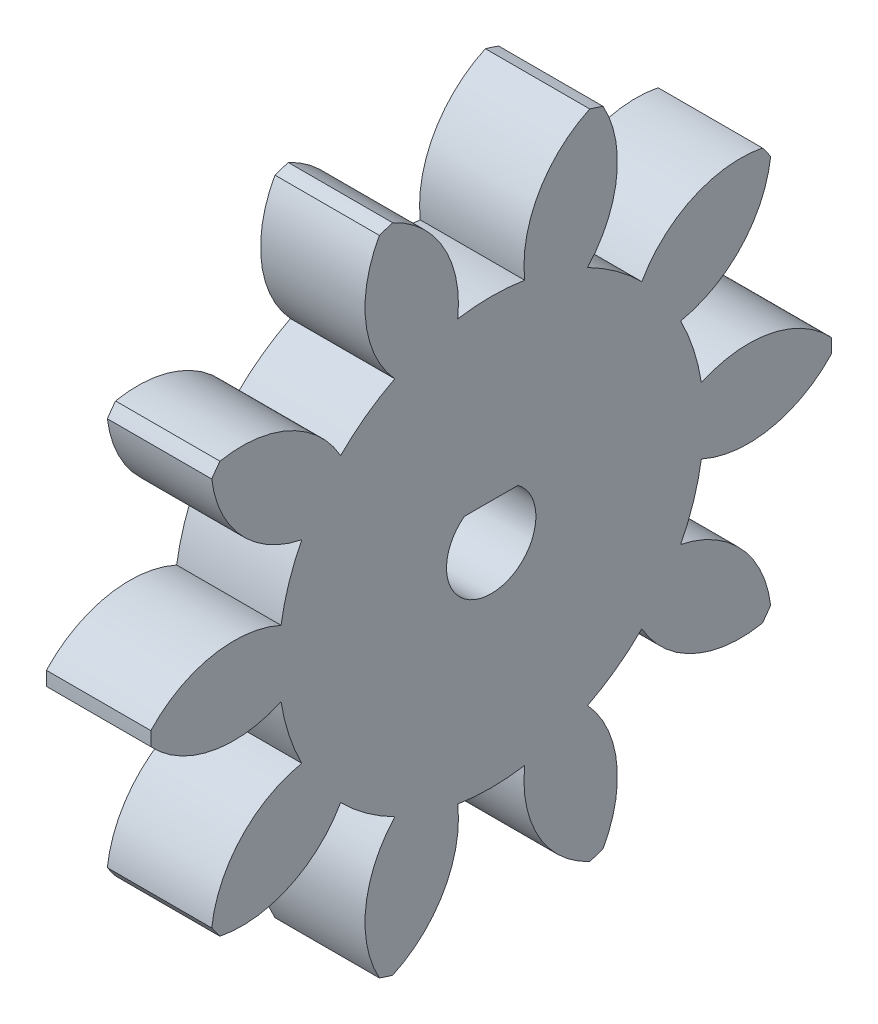
SolidWorks part; units mm, degrees
ref_plane "Plane1" through (0, 0, 0) normal (0, 0, 1) x (1, 0, 0)
ref_plane "Plane2" through (0, 0, 0) normal (0, 1, 0) x (1, 0, 0)
ref_plane "Plane3" through (0, 0, 0) normal (1, 0, 0) x (0, 0, -1)
sketch "HoldingSke" plane through (0, 0, 0) normal (0, 1, 0) x (1, 0, 0)
  line L0 (0, 0) -> (200.1129, -35.2853)
  line L1 (-15, 0) -> (100, 0) construction
  line L2 (0, 0) -> (-2.1039, 2.3779)
  line L3 (0, 0) -> (-11.863, 4.5341)
  line L4 (0, 0) -> (8.5048, 1.4996)
  line L5 (0, 0) -> (-47.5972, -17.7524)
  line L6 (0, 0) -> (-4.8428, -3.2675)
  line L7 (-2.1039, 2.3779) -> (8.8308, 51.9871)
  line L8 (-76.2, 54.61) -> (-71.1708, 54.61)
  line L9 (-71.009, 38.7566) -> (-53.1078, 45.2721)
  line L10 (-76.2, 71.12) -> (104.1128, 71.12)
  line L11 (0, 0) -> (-5.842, 0)
  line L12 (-76.2, 101.6) -> (-76.0857, 101.6)
  line L13 (24.9733, 27.94) -> (52.9518, 28.4284)
  line L14 (24.9733, 27.94) -> (24.9746, 27.94)
  line L15 (24.9733, 27.94) -> (100.4006, 29.5858)
  circle A0 centre (0, 0) radius 2.3812
  circle A1 centre (0, 0) radius 11.905
  circle A2 centre (0, 0) radius 38.1
  circle A3 centre (0, 0) radius 2.3812
  dimension "MHD" = 23.81
  dimension "Hub_dia" = 76.2
  dimension "Bore" = 4.7625
  dimension "MBD" = 4.7625
  dimension "Num_teeth" = 10
  dimension "Pitch" = 203.2
  dimension "Overall_len" = 50.8
  dimension "Show_teeth" = 10
  dimension "Thickness" = 5.842
  dimension "OAL" = 50.8001
  dimension "T_dim" = 5.0292
  dimension "Ap" = 20
  dimension "H" = 19.05
  dimension "Pitch_radius" = 180.3128
  dimension "Width" = 5.842
  dimension "Backlash" = 0.1143
  dimension "Addendum_fac" = 1
  dimension "Dedendum_fac" = 1.25
  dimension "Clearance_fac" = 0.25
  dimension "Dedendum_add" = 0.0013
sketch "BasProSke" plane through (0, 0, 0) normal (0, 1, 0) x (1, 0, 0)
  line L0 (-10, 0) -> (60, 0) construction
  line L1 (0, 0) -> (0, 19.05)
  line L2 (0, 0) -> (5.842, 0)
  line L3 (5.842, 0) -> (5.842, 19.05)
  line L4 (5.842, 19.05) -> (0, 19.05)
  dimension "Thickness" = 5.842
  dimension "Diameter" = 38.1
revolve "Base-Revolve" add sketch "BasProSke" angle 360 about L0
sketch "TooCutSke" plane through (0, 0, 0) normal (1, 0, 0) x (0, 0, -1)
  line L1 (0, 0) -> (0, 107) construction
  line L2 (0, 0) -> (-2.683, 15.6466) construction
  line L3 (0, 0) -> (-9.7093, 29.8821) construction
  line L4 (-2.683, 15.6466) -> (-4.8546, 14.941) construction
  arc A0 (1.8735, 11.7566) -> (-1.8735, 11.7566) centre (0, 0) ccw
  arc A1 (5.5485, 18.2506) -> (-5.5485, 18.2506) centre (0, 0) ccw
  circle A2 centre (0, 0) radius 15.875 construction
  circle A3 centre (0, 0) radius 14.9176 construction
  arc A4 (-1.8735, 11.7566) -> (-5.5485, 18.2506) centre (-8.183, 12.4729) ccw
  arc A5 (5.5485, 18.2506) -> (1.8735, 11.7566) centre (8.183, 12.4729) ccw
  dimension "Root_dia" = 23.81
  dimension "Overcut_dia" = 38.1508
  dimension "Pitch_dia" = 31.75
  dimension "Base_dia" = 29.8352
  dimension "Flank_rad" = 6.35
  dimension "Half_ang" = 18
  dimension "Half_CT" = 2.2834
extrude "ToothCut" cut sketch "TooCutSke" along normal through all
fillet "Breaks" [suppressed] radius 0.0635
fillet "RootFillets" [suppressed] radius 0.795
pattern_circular "TeethCuts" count 10 every 36 about axis through (-10, 0, 0) along (1, 0, 0) of "ToothCut", "RootFillets", "Breaks"
sketch "HubNeaOneSke" plane through (0, 0, 0) normal (-1, 0, 0) x (0, 0, 1)
  circle A0 centre (0, 0) radius 11.905
  dimension "Diameter" = 23.81
extrude "HubNearOne" [suppressed] add sketch "HubNeaOneSke" along normal blind 44.9581
sketch "HubNeaBotSke" plane through (0, 0, 0) normal (-1, 0, 0) x (0, 0, 1)
  circle A0 centre (0, 0) radius 11.905
  dimension "Diameter" = 23.81
extrude "HubNearBoth" [suppressed] add sketch "HubNeaBotSke" along normal blind 22.479
ref_plane "FarPln" through (5.842, 0, 0) normal (1, 0, 0) x (0, 0, -1)
sketch "HubFarSke" plane through (5.842, 0, 0) normal (1, 0, 0) x (0, 0, -1)
  circle A0 centre (0, 0) radius 11.905
  dimension "Diameter" = 23.81
extrude "HubFar" [suppressed] add sketch "HubFarSke" along normal blind 22.479
sketch "BorSke" plane through (0, 0, 0) normal (1, 0, 0) x (0, 0, -1)
  circle A0 centre (0, 0) radius 2.3812
  dimension "Diameter" = 4.7625
extrude "Bore" cut sketch "BorSke" along normal mid plane 101.6001
sketch "KeySke" plane through (0, 0, 0) normal (1, 0, 0) x (0, 0, -1)
  line L0 (-0.127, 0) -> (-0.127, 2.6479)
  line L1 (-0.127, 2.6479) -> (0.127, 2.6479)
  line L2 (0.127, 2.6479) -> (0.127, 0)
  line L3 (0, 0) -> (0, 34) construction
  line L4 (-0.127, 0) -> (0.127, 0)
  dimension "Offset" = 2.648
  dimension "Width" = 0.254
extrude "Keyway" [suppressed] cut sketch "KeySke" along normal mid plane 101.6001
pattern_circular "Keyway2" [suppressed] count 2 every 90 about axis through (-10, 0, 0) along (1, 0, 0)
sketch "Sketch1" plane through (5.842, 0, 0) normal (1, 0, 0) x (0, 0, -1)
  circle A0 centre (0, 0) radius 2.5
  dimension "D1" = 5
extrude "Cut-Extrude1" cut sketch "Sketch1" against normal up to surface (5.842 mm away) up to face at (0, 0, -2.3812)
sketch "Sketch2" plane through (5.842, 0, 0) normal (1, 0, 0) x (0, 0, -1)
  line L0 (-1.5, 2) -> (1.5, 2)
  arc A0 (1.5, 2) -> (-1.5, 2) centre (0, 0) ccw
  point P5 (0, -2.5)
  point P6 (0, 2)
  dimension "D2" = 5
  dimension "D1" = 4.5
extrude "Boss-Extrude1" add sketch "Sketch2" against normal up to surface (5.842 mm away) up to face at (0, 0, -2.5)
equation "' \"Pitch@HoldingSke\" = 4"
equation "' \"Num_teeth@HoldingSke\" = 12"
equation "' \"Ap@HoldingSke\" =  20"
equation "' \"Ap@HoldingSke\" = 20"
equation "' \"Width@HoldingSke\" = 0.5"
equation "' \"Hub_dia@HoldingSke\"= 1"
equation "' \"Hub_dia@HoldingSke\" = 1"
equation "' \"Overall_len@HoldingSke\" = 1.0"
equation "' \"Bore@HoldingSke\" = 0.75"
equation "' \"T_dim@HoldingSke\" = 0.85"
equation "' \"Width@KeySke\" = 0.25"
equation "' \"Show_teeth@HoldingSke\" = 13"
equation "' \"Backlash@HoldingSke\" = 0.009"
equation "' \"Addendum_fac@HoldingSke\" = 1.0"
equation "' \"Dedendum_fac@HoldingSke\" = 1.25"
equation "' \"Dedendum_add@HoldingSke\" = 0.00005"
equation "' \"Clearance_fac@HoldingSke\" = 0.25"
equation "' \"Pitch@HoldingSke\" = 0.5"
equation "' \"Num_teeth@HoldingSke\" = 23"
equation "' \"Show_teeth@HoldingSke\" = 23"
equation "' \"Backlash@HoldingSke\" = 0.0375"
equation "\"Overcut_dia@TooCutSke\" = (\"Num_teeth@HoldingSke\" + 2 * \"Addendum_fac@HoldingSke\") / \"Pitch@HoldingSke\" + 0.002"
equation "\"Pitch_dia@TooCutSke\" = \"Num_teeth@HoldingSke\" / \"Pitch@HoldingSke\""
equation "\"Base_dia@TooCutSke\" = \"Num_teeth@HoldingSke\" / \"Pitch@HoldingSke\" * cos((\"Ap@HoldingSke\"  * 3.14159265 / 180))"
equation "\"Root_dia@TooCutSke\" = (\"Num_teeth@HoldingSke\" + 2) / \"Pitch@HoldingSke\" - 2 * (\"Addendum_fac@HoldingSke\" + \"Dedendum_fac@HoldingSke\") / \"Pitch@HoldingSke\" - \"Dedendum_add@HoldingSke\" * 2"
equation "\"Half_ang@TooCutSke\" = 180 / \"Num_teeth@HoldingSke\""
equation "\"Half_CT@TooCutSke\" = \"Num_teeth@HoldingSke\" / \"Pitch@HoldingSke\" * sin((3.14159265 / 2 / \"Num_teeth@HoldingSke\")) / 2 - 7 * \"Backlash@HoldingSke\" / 4"
equation "\"Flank_rad@TooCutSke\" = \"Num_teeth@HoldingSke\" / \"Pitch@HoldingSke\" / 5"
equation "\"Radius@RootFillets\" = \"Clearance_fac@HoldingSke\" / \"Pitch@HoldingSke\" + \"Dedendum_add@HoldingSke\""
equation "\"Break_rad@Breaks\" = 0.02 / \"Pitch@HoldingSke\""
equation "\"Thickness@HoldingSke\" = \"Width@HoldingSke\""
equation "\"OAL@HoldingSke\" = \"Thickness@HoldingSke\""
equation "\"MHD@HoldingSke\" = (\"Num_teeth@HoldingSke\" + 2) / \"Pitch@HoldingSke\" - 2 * (\"Addendum_fac@HoldingSke\" + \"Dedendum_fac@HoldingSke\")  / \"Pitch@HoldingSke\" - \"Dedendum_add@HoldingSke\" * 2"
equation "\"MBD@HoldingSke\" = (\"Num_teeth@HoldingSke\" + 2) / \"Pitch@HoldingSke\" - 2 * (\"Addendum_fac@HoldingSke\" + \"Dedendum_fac@HoldingSke\")  / \"Pitch@HoldingSke\" - \"Dedendum_add@HoldingSke\" * 2 - 0.002"
equation "\"MHD@HoldingSke\" = ((sgn( \"MHD@HoldingSke\" - \"Hub_dia@HoldingSke\" )-1)*( \"MHD@HoldingSke\" - \"Hub_dia@HoldingSke\" ))/-2+ \"Hub_dia@HoldingSke\""
equation "\"MBD@HoldingSke\" = ((sgn( \"MBD@HoldingSke\" - \"Bore@HoldingSke\" )-1)*( \"MBD@HoldingSke\" - \"Bore@HoldingSke\" ))/-2+ \"Bore@HoldingSke\""
equation "\"OAL@HoldingSke\" = ((sgn( \"OAL@HoldingSke\" - \"Overall_len@HoldingSke\" )+1)*( \"OAL@HoldingSke\" - \"Overall_len@HoldingSke\" ))/2 + \"Overall_len@HoldingSke\" + 0.000002"
equation "\"Num_teeth@TeethCuts\" = int( \"Show_teeth@HoldingSke\" ) + 1"
equation "\"Num_teeth@TeethCuts\" = ((sgn( \"Num_teeth@TeethCuts\" - \"Num_teeth@HoldingSke\" )-1)*( \"Num_teeth@TeethCuts\" - \"Num_teeth@HoldingSke\" ))/-2+ \"Num_teeth@HoldingSke\""
equation "\"Num_teeth@TeethCuts\" = ((sgn( \"Num_teeth@TeethCuts\" - 2.0)+1)*( \"Num_teeth@TeethCuts\" - 2.0))/2 +2.0"
equation "\"Angle@TeethCuts\" = 360.0 / \"Num_teeth@HoldingSke\""
equation "\"Diameter@BasProSke\" = (\"Num_teeth@HoldingSke\" + 2 * \"Addendum_fac@HoldingSke\") / \"Pitch@HoldingSke\""
equation "\"Thickness@BasProSke\"  = \"Thickness@HoldingSke\""
equation "' \"Fillet_rad@BasProSke\" =  \"Thickness@HoldingSke\" * 0.05"
equation "' \"Fillet_rad@BasProSke\" = \"Thickness@HoldingSke\" * 0.05"
equation "\"MHD@HoldingSke\" = ((sgn( \"MHD@HoldingSke\" - \"Root_dia@TooCutSke\" )-1)*( \"MHD@HoldingSke\" - \"Root_dia@TooCutSke\" ))/-2+ \"Root_dia@TooCutSke\""
equation "\"Diameter@HubNeaOneSke\" = \"MHD@HoldingSke\""
equation "\"Length@HubNearOne\" = \"OAL@HoldingSke\" - \"Thickness@BasProSke\""
equation "\"Diameter@HubNeaBotSke\" = \"MHD@HoldingSke\""
equation "\"Length@HubNearBoth\" = ( \"OAL@HoldingSke\" - \"Thickness@BasProSke\" ) / 2.0"
equation "\"Thickness@FarPln\" = \"Thickness@BasProSke\""
equation "\"Diameter@HubFarSke\" = \"MHD@HoldingSke\""
equation "\"Length@HubFar\" = ( \"OAL@HoldingSke\" - \"Thickness@BasProSke\" ) / 2.0"
equation "\"Diameter@BorSke\" = \"MBD@HoldingSke\""
equation "\"D1@Bore\" = \"OAL@HoldingSke\" * 2.0"
equation "\"D1@Keyway\" = \"OAL@HoldingSke\" * 2.0"
equation "\"Offset@KeySke\" = \"T_dim@HoldingSke\" - \"MBD@HoldingSke\" / 2.0"
